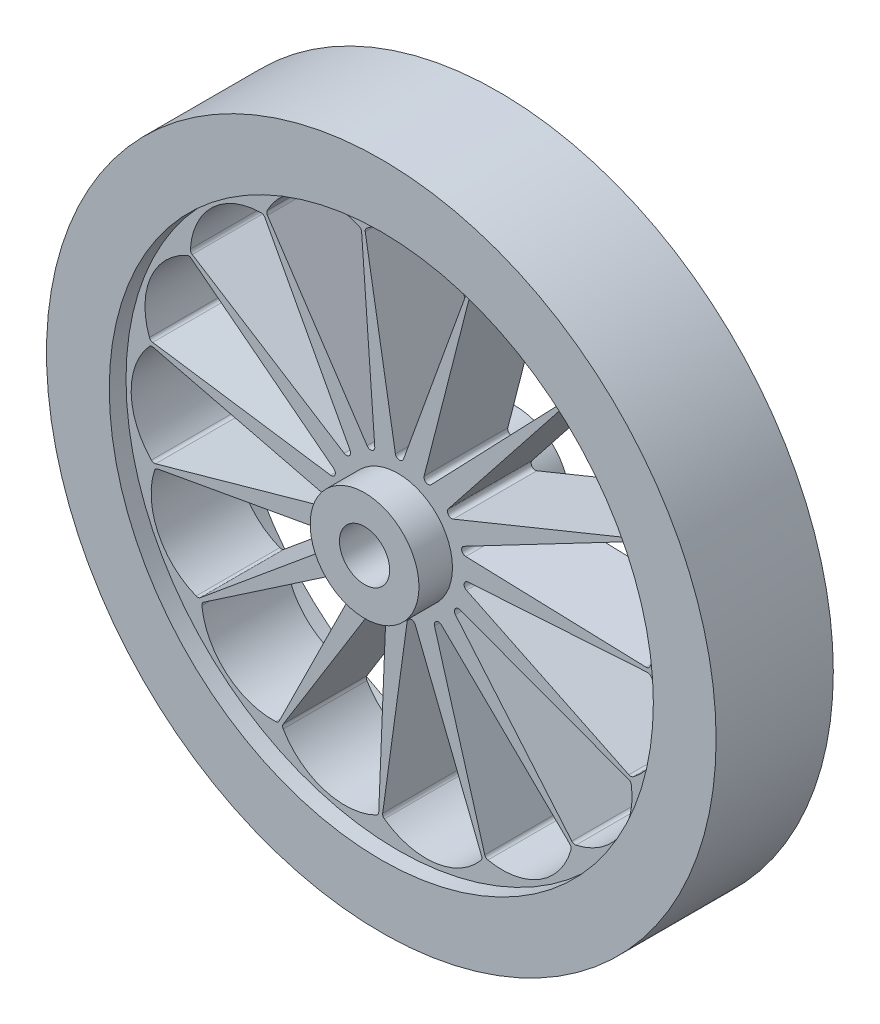
SolidWorks part; units mm, degrees
ref_plane "Front Plane" through (0, 0, 0) normal (0, 0, 1) x (1, 0, 0)
ref_plane "Top Plane" through (0, 0, 0) normal (0, 1, 0) x (1, 0, 0)
ref_plane "Right Plane" through (0, 0, 0) normal (1, 0, 0) x (0, 0, -1)
sketch "Sketch1" plane through (0, 0, 0) normal (1, 0, 0) x (0, 0, -1)
  line L0 (-14, 80) -> (14, 80)
  line L1 (14, 80) -> (14, 65)
  line L2 (14, 65) -> (10, 65)
  line L3 (10, 65) -> (10, 13)
  line L4 (10, 13) -> (18, 13)
  line L5 (18, 13) -> (18, 6)
  line L6 (18, 6) -> (-18, 6)
  line L7 (-18, 6) -> (-18, 13)
  line L8 (-18, 13) -> (-10, 13)
  line L9 (-10, 13) -> (-10, 65)
  line L10 (-10, 65) -> (-14, 65)
  line L11 (-14, 65) -> (-14, 80)
  line L12 (-21.0092, 0) -> (21.2148, 0) construction
  point P6 (14, 13)
  point P16 (0, 80)
  point P17 (0, 6)
  dimension "D1" = 18
  dimension "D2" = 80
  dimension "D3" = 18
  dimension "D4" = 13
  dimension "D5" = 8
  dimension "D6" = 28
  dimension "D7" = 65
  dimension "D8" = 6
  dimension "D9" = 8
revolve "Revolve1" add sketch "Sketch1" angle 360 about L12
sketch "Sketch2" plane through (0, 0, -10) normal (0, 0, -1) x (-1, 0, 0)
  line L0 (0.6377, 16.7476) -> (7.8425, 59.0873)
  line L1 (-1.2889, 16.5763) -> (-15.9006, 57.1204)
  line L2 (7.3945, 15.0403) -> (31.1975, 50.7891)
  line L3 (5.5648, 15.6675) -> (8.7071, 58.6494)
  line L4 (12.8726, 10.7324) -> (49.1581, 33.709)
  line L5 (11.4562, 12.0496) -> (31.8092, 50.0374)
  line L6 (16.125, 4.5688) -> (58.6189, 10.8003)
  line L7 (15.3668, 6.3482) -> (49.4112, 32.7735)
  line L8 (16.5892, -2.3848) -> (57.9439, -13.9758)
  line L9 (16.6203, -0.4509) -> (58.4696, 9.8427)
  line L10 (14.185, -8.9261) -> (47.2499, -36.3355)
  line L11 (15, -7.172) -> (57.418, -14.7899)
  line L12 (9.3281, -13.924) -> (28.386, -52.4124)
  line L13 (10.7861, -12.653) -> (46.4383, -36.8653)
  line L14 (2.8582, -16.5143) -> (4.6138, -59.4267)
  line L15 (4.7071, -15.9461) -> (27.4291, -52.5663)
  line L16 (-4.1058, -16.2491) -> (-19.9561, -56.1656)
  line L17 (-2.1857, -16.4821) -> (3.6771, -59.1781)
  line L18 (-10.3599, -13.1743) -> (-41.0754, -43.193)
  line L19 (-8.7006, -14.1681) -> (-20.7107, -55.5575)
  line L20 (-14.8227, -7.8215) -> (-55.0924, -22.7519)
  line L21 (-13.7111, -9.4044) -> (-41.5175, -42.3305)
  line L22 (-16.7226, -1.1164) -> (-59.5834, 1.6232)
  line L23 (-16.3508, -3.0145) -> (-55.1454, -21.7842)
  line L24 (-15.7309, 5.7818) -> (-53.7719, 25.7176)
  line L25 (-16.1633, 3.8966) -> (-59.2383, 2.5289)
  line L26 (-12.0192, 11.6803) -> (-38.6628, 45.3652)
  line L27 (-13.1811, 10.1339) -> (-53.0883, 26.4046)
  line L28 (-6.2293, 15.5591) -> (-16.8685, 57.1688)
  line L29 (-7.9197, 14.619) -> (-37.7588, 45.7148)
  circle A0 centre (0, 0) radius 13 construction
  circle A1 centre (0, 0) radius 13 construction
  arc A2 (-15.6991, 58.1328) -> (7.476, 60.0402) centre (-3.0878, 46.6479) cw
  arc A3 (0.6377, 16.7476) -> (-1.2889, 16.5763) centre (-0.3481, 16.9154) cw
  arc A4 (7.8425, 59.0873) -> (7.476, 60.0402) centre (6.8567, 59.2551) ccw
  arc A5 (-15.9006, 57.1204) -> (-15.6991, 58.1328) centre (-14.9598, 57.4595) cw
  arc A6 (9.3029, 59.4923) -> (31.2502, 51.8087) centre (16.1525, 43.8709) cw
  arc A7 (7.3945, 15.0403) -> (5.5648, 15.6675) centre (6.5621, 15.5946) cw
  arc A8 (31.1975, 50.7891) -> (31.2502, 51.8087) centre (30.3651, 51.3434) ccw
  arc A9 (8.7071, 58.6494) -> (9.3029, 59.4923) centre (9.7044, 58.5765) cw
  arc A10 (32.6963, 50.5651) -> (49.621, 34.619) centre (32.6, 33.5082) cw
  arc A11 (12.8726, 10.7324) -> (11.4562, 12.0496) centre (12.3377, 11.5773) cw
  arc A12 (49.1581, 33.709) -> (49.621, 34.619) centre (48.6231, 34.5539) ccw
  arc A13 (31.8092, 50.0374) -> (32.6963, 50.5651) centre (32.6906, 49.5652) cw
  arc A14 (50.4363, 32.8948) -> (59.4119, 11.4434) centre (43.4106, 17.3517) cw
  arc A15 (16.125, 4.5688) -> (15.3668, 6.3482) centre (15.9799, 5.5582) cw
  arc A16 (58.6189, 10.8003) -> (59.4119, 11.4434) centre (58.4738, 11.7898) ccw
  arc A17 (49.4112, 32.7735) -> (50.4363, 32.8948) centre (50.0244, 31.9835) cw
  arc A18 (59.4553, 9.5366) -> (58.9299, -13.7109) centre (46.7151, -1.8051) cw
  arc A19 (16.5892, -2.3848) -> (16.6203, -0.4509) centre (16.8591, -1.4219) cw
  arc A20 (57.9439, -13.9758) -> (58.9299, -13.7109) centre (58.2138, -13.0129) ccw
  arc A21 (58.4696, 9.8427) -> (59.4553, 9.5366) centre (58.7084, 8.8717) cw
  arc A22 (58.194, -15.4705) -> (48.2584, -36.4945) centre (41.9421, -20.6498) cw
  arc A23 (14.185, -8.9261) -> (15, -7.172) centre (14.8232, -8.1562) cw
  arc A24 (47.2499, -36.3355) -> (48.2584, -36.4945) centre (47.8881, -35.5656) ccw
  arc A25 (57.418, -14.7899) -> (58.194, -15.4705) centre (57.2412, -15.7742) cw
  arc A26 (46.8705, -37.8027) -> (29.2426, -52.9678) centre (29.917, -35.9239) cw
  arc A27 (9.3281, -13.924) -> (10.7861, -12.653) centre (10.2242, -13.4802) cw
  arc A28 (28.386, -52.4124) -> (29.2426, -52.9678) centre (29.2821, -51.9686) ccw
  arc A29 (46.4383, -36.8653) -> (46.8705, -37.8027) centre (45.8765, -37.6925) cw
  arc A30 (27.4426, -53.5984) -> (5.1705, -60.2825) centre (12.719, -44.9865) cw
  arc A31 (2.8582, -16.5143) -> (4.7071, -15.9461) centre (3.8574, -16.4734) cw
  arc A32 (4.6138, -59.4267) -> (5.1705, -60.2825) centre (5.613, -59.3858) ccw
  arc A33 (27.4291, -52.5663) -> (27.4426, -53.5984) centre (26.5794, -53.0935) cw
  arc A34 (3.2696, -60.1265) -> (-19.7957, -57.1739) centre (-6.6783, -46.2705) cw
  arc A35 (-4.1058, -16.2491) -> (-2.1857, -16.4821) centre (-3.1764, -16.6181) cw
  arc A36 (-19.9561, -56.1656) -> (-19.7957, -57.1739) centre (-19.0266, -56.5346) ccw
  arc A37 (3.6771, -59.1781) -> (3.2696, -60.1265) centre (2.6864, -59.3141) cw
  arc A38 (-21.4687, -56.2581) -> (-41.339, -44.1793) centre (-24.9208, -39.5539) cw
  arc A39 (-10.3599, -13.1743) -> (-8.7006, -14.1681) centre (-9.661, -13.8895) cw
  arc A40 (-41.0754, -43.193) -> (-41.339, -44.1793) centre (-40.3764, -43.9081) ccw
  arc A41 (-20.7107, -55.5575) -> (-21.4687, -56.2581) centre (-21.6711, -55.2788) cw
  arc A42 (-42.4949, -42.6622) -> (-55.7344, -23.5457) centre (-38.8543, -25.998) cw
  arc A43 (-14.8227, -7.8215) -> (-13.7111, -9.4044) centre (-14.4751, -8.7592) cw
  arc A44 (-55.0924, -22.7519) -> (-55.7344, -23.5457) centre (-54.7447, -23.6895) ccw
  arc A45 (-41.5175, -42.3305) -> (-42.4949, -42.6622) centre (-42.2815, -41.6853) cw
  arc A46 (-56.1733, -21.6897) -> (-60.4928, 1.1591) centre (-46.0696, -7.9469) cw
  arc A47 (-16.7226, -1.1164) -> (-16.3508, -3.0145) centre (-16.7863, -2.1143) cw
  arc A48 (-59.5834, 1.6232) -> (-60.4928, 1.1591) centre (-59.6472, 0.6253) ccw
  arc A49 (-55.1454, -21.7842) -> (-56.1733, -21.6897) centre (-55.581, -20.884) cw
  arc A50 (-60.1388, 3.0333) -> (-54.7914, 25.6635) centre (-45.3189, 11.4783) cw
  arc A51 (-15.7309, 5.7818) -> (-16.1633, 3.8966) centre (-16.1951, 4.8961) cw
  arc A52 (-53.7719, 25.7176) -> (-54.7914, 25.6635) centre (-54.2361, 24.8319) ccw
  arc A53 (-59.2383, 2.5289) -> (-60.1388, 3.0333) centre (-59.27, 3.5284) cw
  arc A54 (-53.7058, 27.2317) -> (-39.6162, 45.7305) centre (-36.7323, 28.9188) cw
  arc A55 (-12.0192, 11.6803) -> (-13.1811, 10.1339) centre (-12.8035, 11.0599) cw
  arc A56 (-38.6628, 45.3652) -> (-39.6162, 45.7305) centre (-39.4471, 44.7449) ccw
  arc A57 (-53.0883, 26.4046) -> (-53.7058, 27.2317) centre (-52.7107, 27.3306) cw
  arc A58 (-37.9866, 46.7215) -> (-17.5909, 57.8902) centre (-21.7942, 41.359) cw
  arc A59 (-6.2293, 15.5591) -> (-7.9197, 14.619) centre (-7.1981, 15.3114) cw
  arc A60 (-16.8685, 57.1688) -> (-17.5909, 57.8902) centre (-17.8373, 56.9211) ccw
  arc A61 (-37.7588, 45.7148) -> (-37.9866, 46.7215) centre (-37.0373, 46.4071) cw
  point P10 (0, 13)
  point P157 (0, 0)
  dimension "D1" = 1
  dimension "D2" = 1
  dimension "D3" = 15
extrude "Cut-Extrude1" cut sketch "Sketch2" against normal through all both and the other way through all
